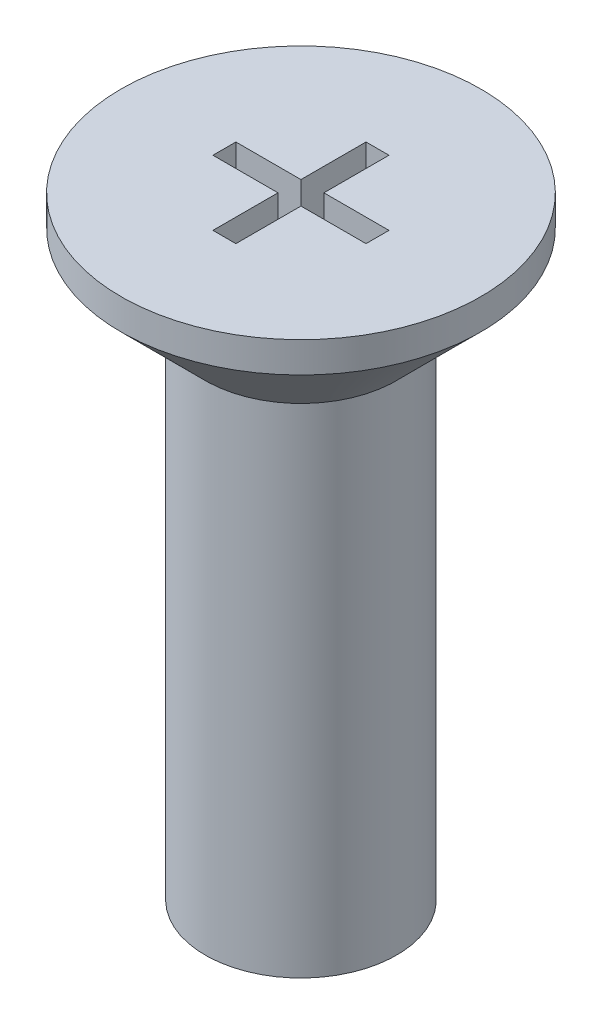
SolidWorks part; units mm, degrees
material "Plain Carbon Steel"
ref_plane "Front Plane" through (0, 0, 0) normal (0, 0, 1) x (1, 0, 0)
ref_plane "Top Plane" through (0, 0, 0) normal (0, 1, 0) x (1, 0, 0)
ref_plane "Right Plane" through (0, 0, 0) normal (1, 0, 0) x (0, 0, -1)
sketch "Sketch1" plane through (0, 0, 0) normal (0, 0, 1) x (1, 0, 0)
  line L0 (0, 0) -> (1.25, 0)
  line L1 (1.25, 0) -> (1.25, 6.5)
  line L2 (1.25, 6.5) -> (2.35, 7.6)
  line L3 (2.35, 7.6) -> (2.35, 8)
  line L4 (2.35, 8) -> (0, 8)
  line L5 (0, 8) -> (0, 0)
  dimension "D1" = 1.25
  dimension "D2" = 8
  dimension "D3" = 45
  dimension "D4" = 2.35
  dimension "D5" = 1.5
revolve "Revolve1" add sketch "Sketch1" angle 360 about L5
sketch "Sketch2" plane through (0, 8, 0) normal (0, 1, 0) x (1, 0, 0)
  line L0 (0, 1) -> (0.15, 1)
  line L1 (0.15, 1) -> (0.15, 0.15)
  line L2 (0.15, 0.15) -> (1, 0.15)
  line L3 (1, 0.15) -> (1, -0.15)
  line L4 (1, -0.15) -> (0.15, -0.15)
  line L5 (0.15, -0.15) -> (0.15, -1)
  line L6 (0.15, -1) -> (-0.15, -1)
  line L7 (-0.15, -1) -> (-0.15, -0.15)
  line L8 (-0.15, -0.15) -> (-1, -0.15)
  line L9 (-1, -0.15) -> (-1, 0.15)
  line L10 (-1, 0.15) -> (-0.15, 0.15)
  line L11 (-0.15, 0.15) -> (-0.15, 1)
  line L12 (-0.15, 1) -> (0, 1)
  dimension "D1" = 2
  dimension "D2" = 2
  dimension "D3" = 1
  dimension "D4" = 1
  dimension "D5" = 0.15
  dimension "D6" = 0.3
  dimension "D7" = 0.3
  dimension "D8" = 0.15
extrude "Cut-Extrude1" cut sketch "Sketch2" against normal blind 1
